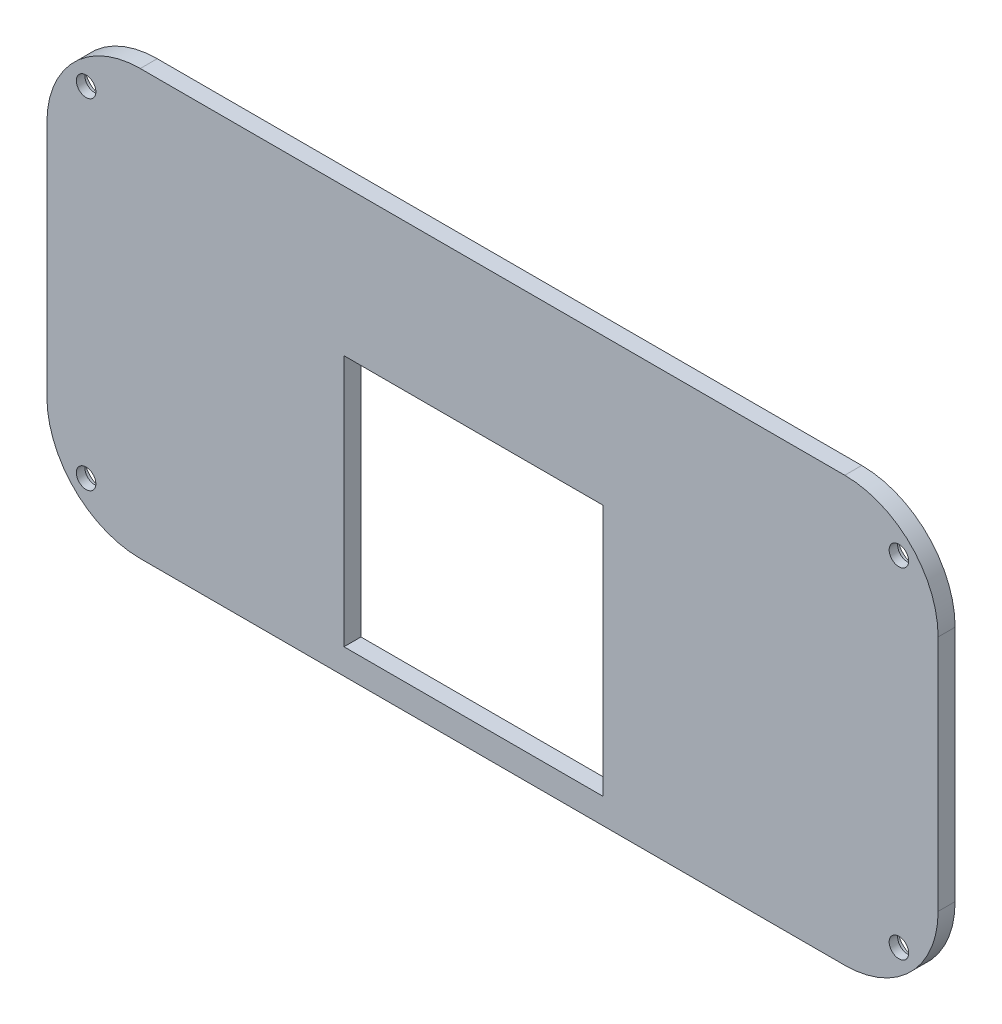
SolidWorks part; units mm, degrees
ref_plane "前视基准面" through (0, 0, 0) normal (0, 0, 1) x (1, 0, 0)
ref_plane "上视基准面" through (0, 0, 0) normal (0, 1, 0) x (1, 0, 0)
ref_plane "右视基准面" through (0, 0, 0) normal (1, 0, 0) x (0, 0, -1)
other "Configuration Table"
sketch "草图1" plane through (0, 0, 0) normal (0, 0, 1) x (1, 0, 0)
  line L1 (-52.5, -25) -> (52.5, -25)
  line L2 (-52.5, -25) -> (-52.5, 25)
  line L3 (-52.5, 25) -> (52.5, 25)
  line L4 (52.5, -25) -> (52.5, 25)
  line L5 (0, 25) -> (0, -25) construction
  line L6 (-52.5, 0) -> (52.5, 0) construction
  point P0 (0, 0)
  dimension "D1" = 105
  dimension "D2" = 50
extrude "凸台-拉伸1" add sketch "草图1" along normal blind 2
fillet "圆角1" radius 11 4 edges at (-52.5, -25, 1) (52.5, -25, 1) (52.5, 25, 1) (-52.5, 25, 1)
sketch "草图3" plane through (0, 0, 0) normal (0, 0, -1) x (-1, 0, 0)
  circle A1 centre (47.8808, -20) radius 2.15
  circle A2 centre (47.8808, 20) radius 2.15
  circle A3 centre (-47.8808, 20) radius 2.15
  circle A4 centre (-47.8808, -20) radius 2.15
  dimension "D1" = 4.3
extrude "切除-拉伸1" cut sketch "草图3" against normal blind 1
sketch "草图4" plane through (0, 0, 1) normal (0, 0, -1) x (-1, 0, 0)
  circle A0 centre (47.8808, -20) radius 1.15
  circle A1 centre (-47.8808, -20) radius 1.15
  circle A2 centre (47.8808, 20) radius 1.15
  circle A3 centre (-47.8808, 20) radius 1.15
  circle A4 centre (-47.8808, 20) radius 2.15 construction
  circle A5 centre (47.8808, 20) radius 2.15 construction
  dimension "D1" = 2.3
extrude "切除-拉伸2" cut sketch "草图4" against normal up to next
sketch "草图5" plane through (0, 0, 0) normal (0, 0, -1) x (-1, 0, 0)
  line L0 (41.5, -25) -> (-41.5, -25) construction
  line L1 (17.5, -22) -> (-13, -22)
  line L2 (17.5, -22) -> (17.5, 7.7)
  line L3 (17.5, 7.7) -> (-13, 7.7)
  line L4 (-13, -22) -> (-13, 7.7)
  line L5 (2.25, 7.7) -> (2.25, -22) construction
  line L6 (17.5, -7.15) -> (-13, -7.15) construction
  line L7 (52.5, 14) -> (52.5, -14) construction
  point P0 (2.25, -7.15)
  dimension "D1" = 3
  dimension "D2" = 35
  dimension "D3" = 30.5
  dimension "D4" = 29.7
extrude "切除-拉伸3" cut sketch "草图5" against normal up to next
